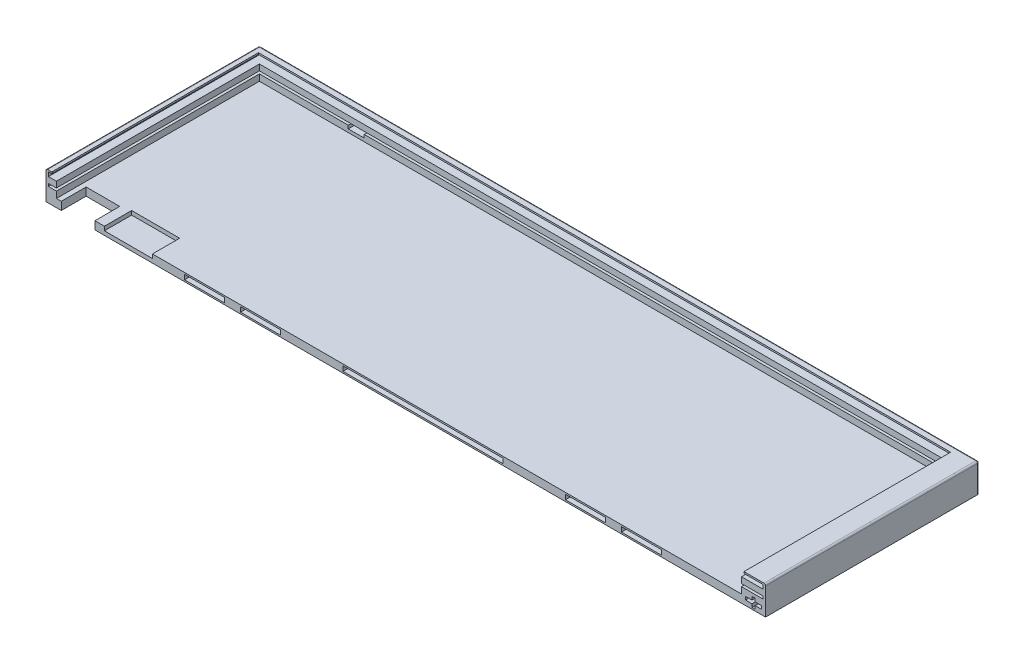
SolidWorks part; units mm, degrees
ref_plane "前视基准面" through (0, 0, 0) normal (0, 0, 1) x (1, 0, 0)
ref_plane "上视基准面" through (0, 0, 0) normal (0, 1, 0) x (1, 0, 0)
ref_plane "右视基准面" through (0, 0, 0) normal (1, 0, 0) x (0, 0, -1)
sketch "草图1" plane through (0, 0, 0) normal (1, 0, 0) x (0, 0, -1)
  line L0 (0, 0) -> (-4.2, 0)
  line L2 (-4.2, -1) -> (-1.5, -1)
  line L3 (-1.5, -1) -> (-1.5, -3.55)
  line L4 (-1.5, -3.55) -> (-6.5, -3.55)
  line L5 (-6.5, -3.55) -> (-6.5, -7.25)
  line L6 (-6.5, -7.25) -> (-1.5, -7.25)
  line L7 (-1.5, -7.25) -> (-1.5, -8.9)
  line L8 (-1.5, -8.9) -> (-6.5, -8.9)
  line L9 (-6.5, -8.9) -> (-6.5, -12.9)
  line L10 (-6.5, -12.9) -> (-133.326, -12.9)
  line L11 (-133.326, -12.9) -> (-133.326, -17.9)
  line L12 (-133.326, -17.9) -> (0, -17.9)
  line L13 (0, -17.9) -> (0, 0)
  line L15 (-4.2, 0) -> (-4.2, -1)
extrude "凸台-拉伸1" add sketch "草图1" along normal blind 449.532
sketch "草图3" plane through (0, 0, 0) normal (0, 0, -1) x (-1, 0, 0)
  line L0 (-449.532, 0) -> (-436.032, 0)
  line L1 (-449.532, 0) -> (0, 0) construction
  line L3 (-436.032, -1) -> (-448.032, -1)
  line L4 (-448.032, -1) -> (-448.032, -3.55)
  line L5 (-448.032, -3.55) -> (-434.532, -3.55)
  line L6 (-434.532, -3.55) -> (-434.532, -7.25)
  line L7 (-434.532, -7.25) -> (-448.032, -7.25)
  line L8 (-448.032, -7.25) -> (-448.032, -8.9)
  line L9 (-448.032, -8.9) -> (-434.532, -8.9)
  line L10 (-434.532, -8.9) -> (-434.532, -17.9)
  line L11 (-449.532, -17.9) -> (0, -17.9) construction
  line L12 (-434.532, -17.9) -> (-449.532, -17.9)
  line L13 (-449.532, -17.9) -> (-449.532, 0)
  line L15 (-436.032, -1) -> (-436.032, 0)
extrude "凸台-拉伸2" add sketch "草图3" against normal blind 133.326
sketch "草图4" plane through (0, 0, 0) normal (0, 0, -1) x (-1, 0, 0)
  line L0 (0, 0) -> (-3.6, 0)
  line L1 (-449.532, 0) -> (0, 0) construction
  line L4 (-3.6, -1) -> (-1.5, -1)
  line L5 (-1.5, -1) -> (-1.5, -3.55)
  line L6 (-1.5, -3.55) -> (-6.5, -3.55)
  line L7 (-6.5, -3.55) -> (-6.5, -7.25)
  line L8 (-6.5, -7.25) -> (-1.5, -7.25)
  line L9 (-1.5, -7.25) -> (-1.5, -8.9)
  line L10 (-1.5, -8.9) -> (-6.5, -8.9)
  line L11 (-6.5, -8.9) -> (-6.5, -17.9)
  line L12 (-449.532, -17.9) -> (0, -17.9) construction
  line L13 (-6.5, -17.9) -> (0, -17.9)
  line L14 (0, -17.9) -> (0, 0)
  line L15 (-3.6, -1) -> (-3.6, 0)
extrude "凸台-拉伸3" add sketch "草图4" against normal blind 133.326
sketch "草图6" plane through (0, 0, 6.5) normal (0, 0, 1) x (1, 0, 0)
  line L1 (434.532, -8.9) -> (6.5, -8.9) construction
  line L2 (62, -8.9) -> (62, -10.9)
  line L3 (62, -10.9) -> (72, -10.9)
  line L4 (72, -10.9) -> (72, -8.9)
  line L5 (72, -8.9) -> (62, -8.9)
extrude "切除-拉伸4" cut sketch "草图6" against normal blind 5
sketch "草图7" plane through (434.532, 0, 0) normal (-1, 0, 0) x (0, 0, 1)
  line L1 (133.326, -8.9) -> (6.5, -8.9) construction
  line L3 (16, -8.9) -> (16, -11.4)
  line L4 (16, -11.4) -> (31, -11.4)
  line L5 (31, -11.4) -> (31, -8.9)
  line L6 (31, -8.9) -> (16, -8.9)
extrude "切除-拉伸5" cut sketch "草图7" against normal blind 8.5
sketch "草图9" plane through (0, 0, 133.326) normal (0, 0, 1) x (1, 0, 0)
  line L10 (185.515, -13.9) -> (185.515, -16.9)
  line L12 (185.515, -13.9) -> (285.515, -13.9)
  line L14 (185.515, -16.9) -> (285.515, -16.9)
  line L15 (285.515, -16.9) -> (285.515, -13.9)
  line L16 (86.5, -13.9) -> (86.5, -16.9)
  line L17 (349.532, -13.9) -> (349.532, -16.9)
  line L19 (86.5, -13.9) -> (111.5, -13.9)
  line L20 (86.5, -16.9) -> (111.5, -16.9)
  line L21 (111.5, -16.9) -> (111.5, -13.9)
  line L23 (121.5, -13.9) -> (146.5, -13.9)
  line L24 (121.5, -13.9) -> (121.5, -16.9)
  line L25 (121.5, -16.9) -> (146.5, -16.9)
  line L27 (384.532, -16.9) -> (359.532, -16.9)
  line L28 (384.532, -13.9) -> (359.532, -13.9)
  line L29 (359.532, -13.9) -> (359.532, -16.9)
  line L30 (349.532, -16.9) -> (324.532, -16.9)
  line L31 (349.532, -13.9) -> (324.532, -13.9)
  line L33 (437.032, -12.9) -> (437.032, -14.9)
  line L34 (437.032, -12.9) -> (441.032, -12.9)
  line L35 (441.032, -12.9) -> (441.032, -10.9)
  line L36 (441.032, -10.9) -> (443.032, -10.9)
  line L37 (443.032, -10.9) -> (443.032, -12.9)
  line L38 (443.032, -12.9) -> (447.032, -12.9)
  line L39 (447.032, -12.9) -> (447.032, -14.9)
  line L40 (447.032, -14.9) -> (443.032, -14.9)
  line L41 (443.032, -14.9) -> (443.032, -16.9)
  line L42 (443.032, -16.9) -> (441.032, -16.9)
  line L43 (441.032, -16.9) -> (441.032, -14.9)
  line L44 (441.032, -14.9) -> (437.032, -14.9)
  line L45 (146.5, -13.9) -> (146.5, -16.9)
  line L46 (324.532, -13.9) -> (324.532, -16.9)
  line L47 (384.532, -13.9) -> (384.532, -16.9)
extrude "切除-拉伸7" cut sketch "草图9" against normal blind 30
sketch "草图10" plane through (0, 0, 133.326) normal (0, 0, 1) x (1, 0, 0)
  line L0 (9.5531, -17.9) -> (9.5531, -12.9)
  line L1 (434.532, -12.9) -> (6.5, -12.9) construction
  line L2 (30.5531, -12.9) -> (30.5531, -17.9)
  line L3 (449.532, -17.9) -> (0, -17.9) construction
  line L4 (30.5531, -17.9) -> (9.5531, -17.9)
  line L5 (9.5531, -12.9) -> (30.5531, -12.9)
extrude "切除-拉伸8" cut sketch "草图10" against normal blind 15.5
sketch "草图11" plane through (0, 0, 133.326) normal (0, 0, 1) x (1, 0, 0)
  line L1 (434.532, -12.9) -> (30.5531, -12.9) construction
  line L6 (36.5, -12.9) -> (66.5, -12.9)
  line L7 (66.5, -12.9) -> (66.5, -15.4)
  line L8 (66.5, -15.4) -> (36.5, -15.4)
  line L9 (36.5, -15.4) -> (36.5, -12.9)
extrude "切除-拉伸9" cut sketch "草图11" against normal blind 17
fillet "圆角1" radius 1 1 edges at (0, 0, 66.663)
fillet "圆角2" radius 1 3 edges at (0, -9.45, 0) (0.2929, -0.2929, 0) (225.266, 0, 0)
fillet "圆角4" radius 1 3 edges at (449.532, -9.45, 0) (449.532, -0.2929, 0.2929) (449.532, 0, 67.163)
